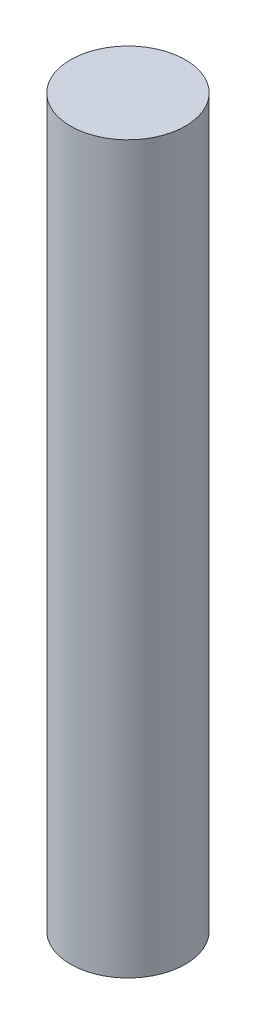
SolidWorks part; units mm, degrees
ref_plane "Front Plane" through (0, 0, 0) normal (0, 0, 1) x (1, 0, 0)
ref_plane "Top Plane" through (0, 0, 0) normal (0, 1, 0) x (1, 0, 0)
ref_plane "Right Plane" through (0, 0, 0) normal (1, 0, 0) x (0, 0, -1)
sketch "Sketch1" plane through (0, 0, 0) normal (0, 1, 0) x (1, 0, 0)
  circle A0 centre (0, 0) radius 4.75
extrude "Boss-Extrude1" add sketch "Sketch1" along normal blind 60
